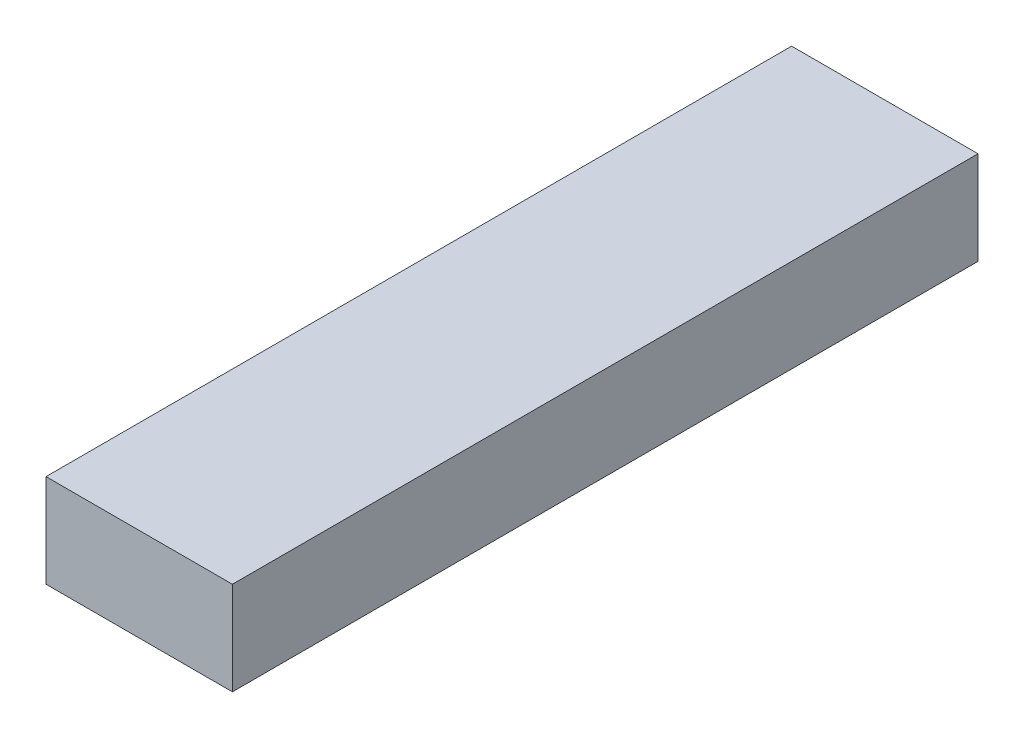
SolidWorks part; units mm, degrees
material "Beech"
ref_plane "Front Plane" through (0, 0, 0) normal (0, 0, 1) x (1, 0, 0)
ref_plane "Top Plane" through (0, 0, 0) normal (0, 1, 0) x (1, 0, 0)
ref_plane "Right Plane" through (0, 0, 0) normal (1, 0, 0) x (0, 0, -1)
sketch "Sketch1" plane through (0, 0, 0) normal (0, 1, 0) x (1, 0, 0)
  line L1 (0, 0) -> (304.8, 0)
  line L2 (0, 0) -> (0, 304.8)
  line L3 (0, 304.8) -> (304.8, 304.8)
  line L4 (304.8, 0) -> (304.8, 304.8)
  dimension "D1" = 304.8
  dimension "D2" = 304.8
extrude "Boss-Extrude1" add sketch "Sketch1" along normal blind 6.35
sketch "Sketch2" plane through (0, 6.35, 0) normal (0, 1, 0) x (1, 0, 0)
  line L1 (304.8, 304.8) -> (0, 304.8) construction
  line L2 (12.7, 304.8) -> (12.7, 254)
  line L3 (12.7, 254) -> (0, 254)
  line L4 (0, 304.8) -> (0, 0) construction
  line L6 (0, 254) -> (0, 0)
  line L7 (0, 0) -> (304.8, 0)
  line L8 (304.8, 0) -> (304.8, 304.8)
  line L9 (304.8, 304.8) -> (12.7, 304.8)
  dimension "D1" = 12.7
  dimension "D2" = 50.8
extrude "Cut-Extrude2" cut sketch "Sketch2" against normal blind 6.35 contours L3 L6 L7 L8 L9 L2
